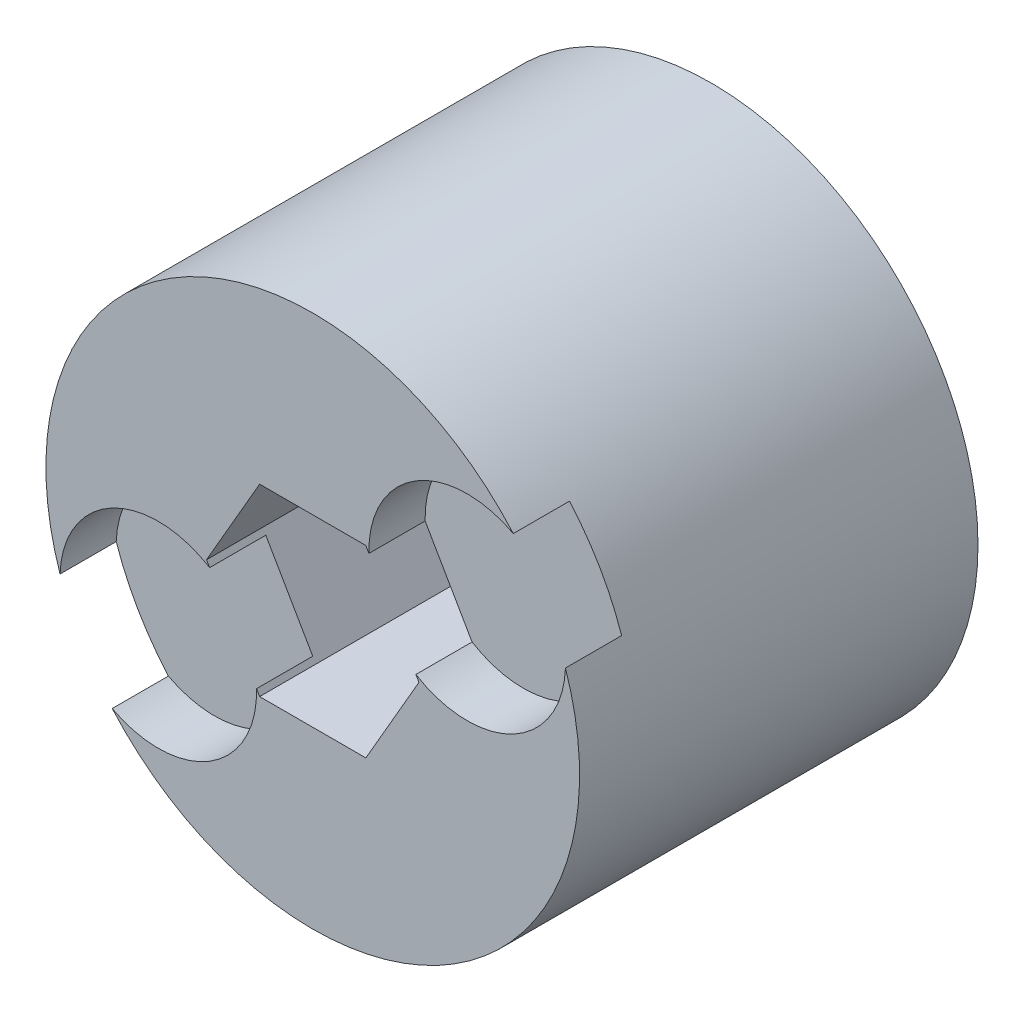
SolidWorks part; units mm, degrees
material "Nylon 6/10"
ref_plane "Front Plane" through (0, 0, 0) normal (0, 0, 1) x (1, 0, 0)
ref_plane "Top Plane" through (0, 0, 0) normal (0, 1, 0) x (1, 0, 0)
ref_plane "Right Plane" through (0, 0, 0) normal (1, 0, 0) x (0, 0, -1)
sketch "Sketch1" plane through (0, 0, 0) normal (0, 0, 1) x (1, 0, 0)
  line L19 (1.8908, -3.275) -> (-1.8908, -3.275) construction
  line L20 (-1.8908, -3.275) -> (-3.7816, 0) construction
  line L21 (-3.7816, 0) -> (-1.8908, 3.275) construction
  line L22 (-1.8908, 3.275) -> (1.8908, 3.275) construction
  line L23 (1.8908, 3.275) -> (3.7816, 0) construction
  line L24 (3.7816, 0) -> (1.8908, -3.275) construction
  line L25 (1.8908, -3.275) -> (-1.8908, -3.275)
  line L26 (-1.8908, -3.275) -> (-3.7816, 0)
  line L27 (-3.7816, 0) -> (-1.8908, 3.275)
  line L28 (-1.8908, 3.275) -> (1.8908, 3.275)
  line L29 (1.8908, 3.275) -> (3.7816, 0)
  line L30 (3.7816, 0) -> (1.8908, -3.275)
  arc A3 (9.0139, 3) -> (-1.9089, 9.3062) centre (0, 0) ccw construction
  arc A6 (9.0139, 3) -> (-1.9089, 9.3062) centre (0, 0) ccw construction
  circle A7 centre (0, 0) radius 9.5
extrude "Boss-Extrude1" add sketch "Sketch1" along normal offset from surface (14.185 mm away) 0.2
sketch "Sketch2" plane through (0, 0, 14.185) normal (0, 0, 1) x (1, 0, 0)
  circle A0 centre (5.4993, 3.175) radius 2.85 construction
  circle A1 centre (5.4993, 3.175) radius 2.85 construction
  circle A2 centre (-5.4993, -3.175) radius 2.85 construction
  circle A3 centre (-5.4993, -3.175) radius 2.85 construction
  circle A4 centre (5.4993, 3.175) radius 3.5
  circle A5 centre (-5.4993, -3.175) radius 3.5
  dimension "D1" = 7
extrude "Cut-Extrude1" cut sketch "Sketch2" against normal blind 2
